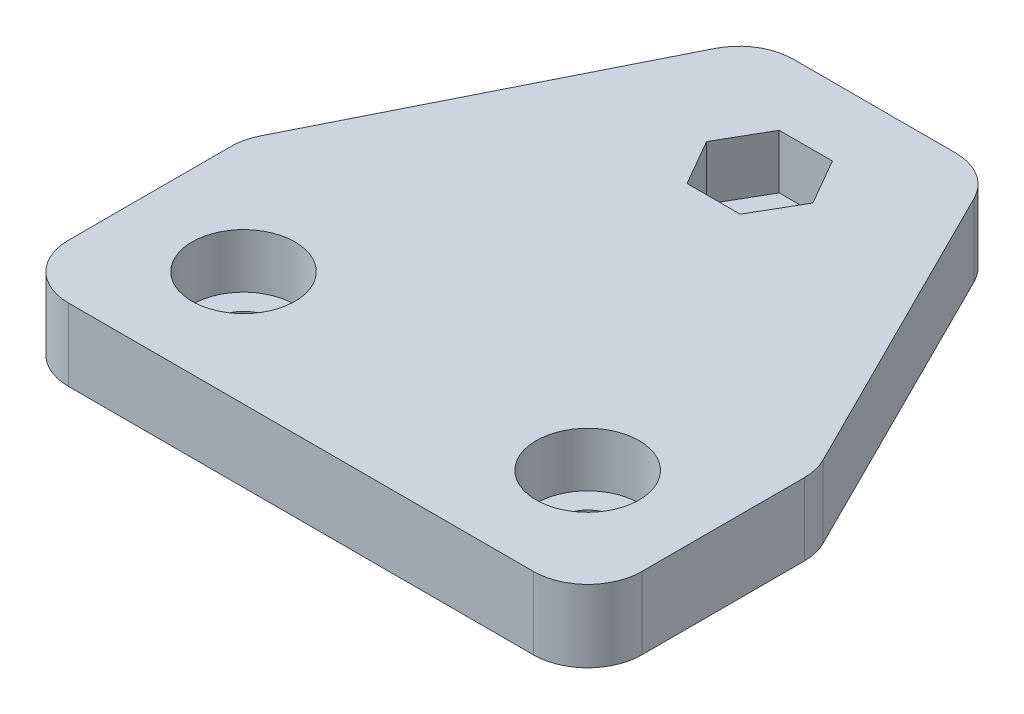
SolidWorks part; units mm, degrees
ref_plane "Front Plane" through (0, 0, 0) normal (0, 0, 1) x (1, 0, 0)
ref_plane "Top Plane" through (0, 0, 0) normal (0, 1, 0) x (1, 0, 0)
ref_plane "Right Plane" through (0, 0, 0) normal (1, 0, 0) x (0, 0, -1)
sketch "Sketch1" plane through (0, 0, 0) normal (0, 1, 0) x (1, 0, 0)
  line L0 (-31.75, 0) -> (31.75, 0)
  line L1 (-31.75, 0) -> (-31.75, 25.4)
  line L2 (-31.75, 25.4) -> (-12.7, 63.5)
  line L3 (-12.7, 63.5) -> (12.7, 63.5)
  line L4 (12.7, 63.5) -> (31.75, 25.4)
  line L5 (31.75, 25.4) -> (31.75, 0)
  point P0 (0, 63.5)
  point P4 (0, 0)
  dimension "D1" = 25.4
  dimension "D2" = 63.5
  dimension "D3" = 25.4
  dimension "D4" = 63.5
extrude "Boss-Extrude1" add sketch "Sketch1" along normal blind 8
sketch "Sketch2" plane through (0, 8, 0) normal (0, 1, 0) x (1, 0, 0)
  line L0 (-31.75, 12.7) -> (0, 12.7) construction
  line L3 (0, 0) -> (0, 63.5) construction
  line L4 (12.7, 63.5) -> (-12.7, 63.5) construction
  line L5 (-31.75, 25.4) -> (-31.75, 0) construction
  line L6 (0, 12.7) -> (31.75, 12.7) construction
  line L7 (31.75, 0) -> (31.75, 25.4) construction
  circle A2 centre (0, 50.8) radius 3.1
  circle A3 centre (-19.05, 12.7) radius 3.1
  circle A4 centre (19.05, 12.7) radius 3.1
  dimension "D4" = 6.2
  dimension "D1" = 12.7
  dimension "D2" = 12.7
  dimension "D3" = 12.7
extrude "Cut-Extrude1" cut sketch "Sketch2" against normal through all both and the other way through all
fillet "Fillet1" radius 6 6 edges at (-12.7, 4, -63.5) (12.7, 4, -63.5) (31.75, 4, -25.4) (31.75, 4, 0) (-31.75, 4, 0) (-31.75, 4, -25.4)
sketch "Sketch3" plane through (0, 8, 0) normal (0, 1, 0) x (1, 0, 0)
  line L19 (5.889, 50.8) -> (2.9445, 55.9)
  line L20 (2.9445, 55.9) -> (-2.9445, 55.9)
  line L21 (-2.9445, 55.9) -> (-5.889, 50.8)
  line L22 (-5.889, 50.8) -> (-2.9445, 45.7)
  line L23 (-2.9445, 45.7) -> (2.9445, 45.7)
  line L24 (2.9445, 45.7) -> (5.889, 50.8)
  circle A0 centre (0, 50.8) radius 5.1 construction
  circle A1 centre (-19.05, 12.7) radius 5.7
  circle A2 centre (19.05, 12.7) radius 5.7
  dimension "D1" = 10.2
  dimension "D2" = 11.4
extrude "Cut-Extrude2" cut sketch "Sketch3" against normal blind 6 and the other way through all
